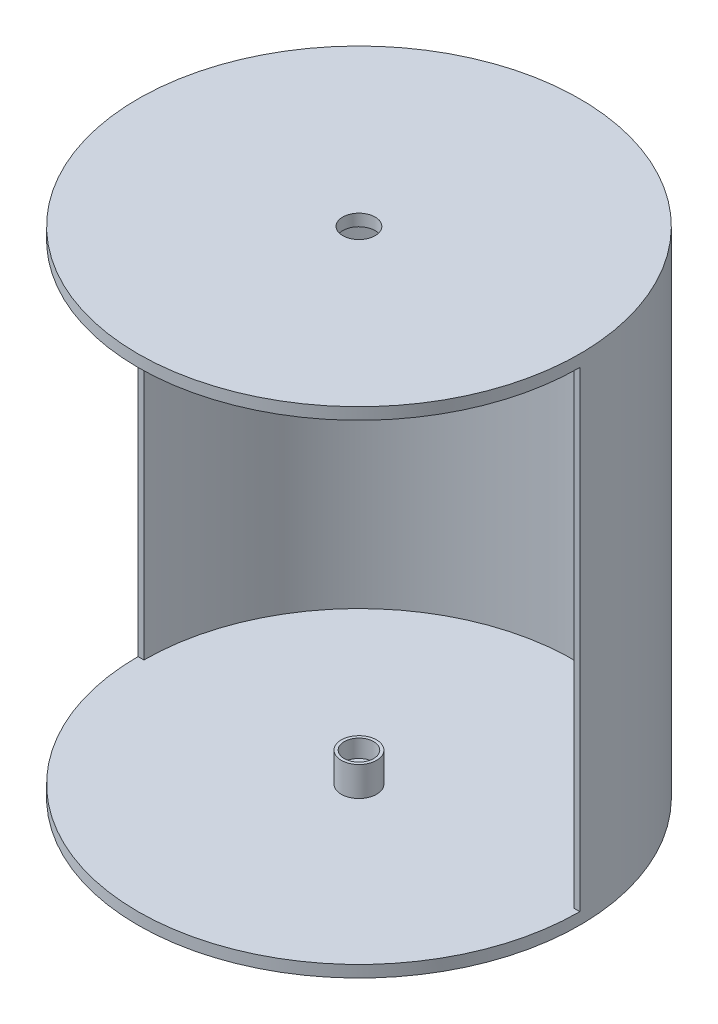
SolidWorks part; units mm, degrees
ref_plane "Front Plane" through (0, 0, 0) normal (0, 0, 1) x (1, 0, 0)
ref_plane "Top Plane" through (0, 0, 0) normal (0, 1, 0) x (1, 0, 0)
ref_plane "Right Plane" through (0, 0, 0) normal (1, 0, 0) x (0, 0, -1)
sketch "Sketch1" plane through (0, 0, 0) normal (0, 1, 0) x (1, 0, 0)
  circle A1 centre (0, 0) radius 37.5
  point P7 (0, 0)
  point P8 (0, 0)
  dimension "D1" = 75
extrude "Boss-Extrude1" add sketch "Sketch1" along normal blind 2
sketch "Sketch2" plane through (0, 2, 0) normal (0, 1, 0) x (1, 0, 0)
  circle A0 centre (0, 0) radius 3
extrude "Boss-Extrude2" add sketch "Sketch2" along normal blind 5
sketch "Sketch3" plane through (0, 7, 0) normal (0, 1, 0) x (1, 0, 0)
  circle A0 centre (0, 0) radius 2.5
extrude "Cut-Extrude1" cut sketch "Sketch3" against normal blind 3
sketch "Sketch4" plane through (0, 2, 0) normal (0, 1, 0) x (1, 0, 0)
  line L0 (-37.5, 0) -> (-36.5, 0)
  line L1 (36.5, 0) -> (37.5, 0)
  arc A0 (37.5, 0) -> (-37.5, 0) centre (0, 0) ccw
  arc A1 (36.5, 0) -> (-36.5, 0) centre (0, 0) ccw
  dimension "D1" = 37.5
  dimension "D2" = 36.5
extrude "Boss-Extrude3" add sketch "Sketch4" along normal blind 80
sketch "Sketch5" plane through (0, 82, 0) normal (0, 1, 0) x (1, 0, 0)
  circle A0 centre (0, 0) radius 37.5
  circle A1 centre (0, 0) radius 2.75
  dimension "D1" = 75
extrude "Boss-Extrude4" add sketch "Sketch5" along normal blind 2
